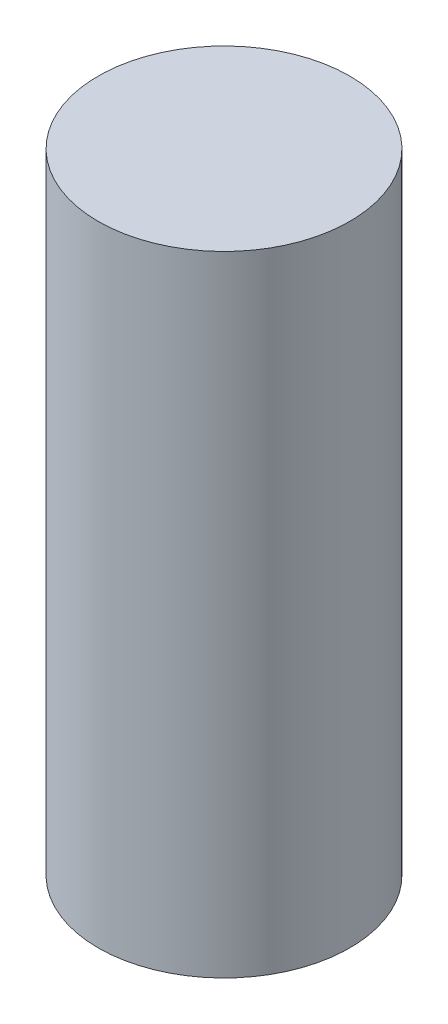
SolidWorks part; units mm, degrees
ref_plane "Front Plane" through (0, 0, 0) normal (0, 0, 1) x (1, 0, 0)
ref_plane "Top Plane" through (0, 0, 0) normal (0, 1, 0) x (1, 0, 0)
ref_plane "Right Plane" through (0, 0, 0) normal (1, 0, 0) x (0, 0, -1)
sketch "Sketch1" plane through (0, 0, 0) normal (0, 1, 0) x (1, 0, 0)
  circle A0 centre (0, 0) radius 2
  dimension "D1" = 4
extrude "Boss-Extrude1" add sketch "Sketch1" along normal blind 10
